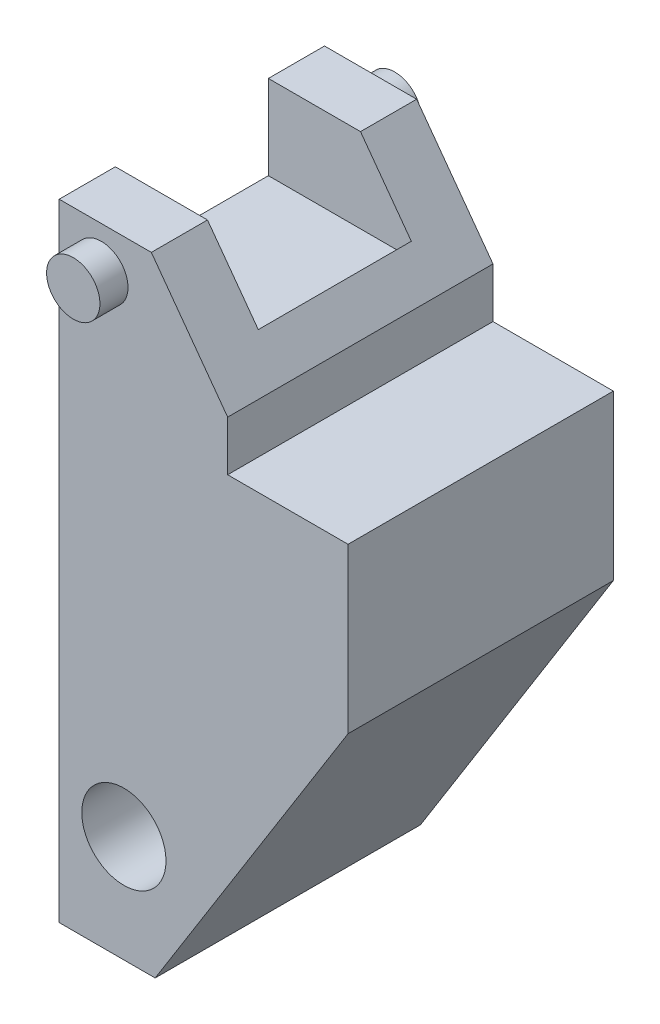
SolidWorks part; units mm, degrees
ref_plane "Front Plane" through (0, 0, 0) normal (0, 0, 1) x (1, 0, 0)
ref_plane "Top Plane" through (0, 0, 0) normal (0, 1, 0) x (1, 0, 0)
ref_plane "Right Plane" through (0, 0, 0) normal (1, 0, 0) x (0, 0, -1)
sketch "Sketch1" plane through (0, 0, 0) normal (0, 0, 1) x (1, 0, 0)
  line L1 (-1.2284, 16.3534) -> (19.3477, 16.3534)
  line L2 (-1.2284, 16.3534) -> (-1.2284, -17.2747)
  line L3 (-1.2284, -17.2747) -> (19.3477, -17.2747)
  line L4 (19.3477, 16.3534) -> (19.3477, -17.2747)
  circle A0 centre (8.5253, 7.418) radius 5.1
  circle A1 centre (3.3782, -9.6738) radius 1.6
  dimension "D1" = 17.85
  dimension "D2" = 10.2
  dimension "D3" = 3.2
extrude "Boss-Extrude1" add sketch "Sketch1" along normal blind 18.9
sketch "Sketch3" plane through (0, 16.3534, 0) normal (0, 1, 0) x (1, 0, 0)
  line L0 (19.3477, -18.9) -> (-1.2284, -18.9) construction
  line L1 (-1.2284, 0) -> (10.7716, 0)
  line L2 (-1.2284, 0) -> (-1.2284, -18.9)
  line L3 (-1.2284, -18.9) -> (10.7716, -18.9)
  line L4 (10.7716, 0) -> (10.7716, -18.9)
  dimension "D1" = 12
extrude "Boss-Extrude3" add sketch "Sketch3" along normal blind 11
sketch "Sketch4" plane through (0, 0, 18.9) normal (0, 0, 1) x (1, 0, 0)
  line L0 (-1.2284, 27.3534) -> (10.7716, 27.3534) construction
  line L1 (-1.2284, 27.3534) -> (-1.2284, -17.2747) construction
  circle A0 centre (1.7716, 24.3534) radius 1.9
  dimension "D1" = 3.8
  dimension "D2" = 3
  dimension "D3" = 3
extrude "Boss-Extrude6" add sketch "Sketch4" along normal blind 2
sketch "Sketch5" plane through (0, 0, 0) normal (0, 0, -1) x (-1, 0, 0)
  line L0 (1.2284, 27.3534) -> (1.2284, -17.2747) construction
  line L1 (-10.7716, 27.3534) -> (1.2284, 27.3534) construction
  circle A0 centre (-1.7716, 24.3534) radius 1.9
  dimension "D1" = 3.8
  dimension "D2" = 3
  dimension "D3" = 3
extrude "Boss-Extrude7" add sketch "Sketch5" along normal blind 2
sketch "Sketch6" plane through (0, 0, 18.9) normal (0, 0, 1) x (1, 0, 0)
  line L0 (5.6068, -17.2747) -> (19.3477, 4.6661)
  line L1 (-1.2284, -17.2747) -> (19.3477, -17.2747) construction
  line L2 (19.3477, -17.2747) -> (19.3477, 16.3534) construction
  line L3 (19.3477, 4.6661) -> (19.3477, -17.2747)
  line L4 (19.3477, -17.2747) -> (5.6068, -17.2747)
extrude "Cut-Extrude1" cut sketch "Sketch6" against normal through all
sketch "Sketch7" plane through (0, 0, 18.9) normal (0, 0, 1) x (1, 0, 0)
  line L0 (5.3343, 27.3534) -> (10.7716, 19.9086)
  line L1 (-1.2284, 27.3534) -> (10.7716, 27.3534) construction
  line L2 (10.7716, 27.3534) -> (10.7716, 16.3534) construction
  line L3 (10.7716, 19.9086) -> (10.7716, 27.3534)
  line L4 (10.7716, 27.3534) -> (5.3343, 27.3534)
extrude "Cut-Extrude2" cut sketch "Sketch7" against normal through all
sketch "Sketch8" plane through (0, 27.3534, 0) normal (0, 1, 0) x (1, 0, 0)
  line L0 (-1.2284, 0) -> (-1.2284, -18.9) construction
  line L1 (-1.2284, -14.9) -> (8.9531, -14.9)
  line L2 (-1.2284, -14.9) -> (-1.2284, -4)
  line L3 (-1.2284, -4) -> (8.9531, -4)
  line L4 (8.9531, -14.9) -> (8.9531, -4)
  line L5 (5.3343, 0) -> (-1.2284, 0) construction
  line L6 (-1.2284, -18.9) -> (5.3343, -18.9) construction
  dimension "D1" = 4
  dimension "D2" = 4
extrude "Cut-Extrude3" cut sketch "Sketch8" against normal blind 6
sketch "Sketch9" plane through (0, 0, 18.9) normal (0, 0, 1) x (1, 0, 0)
  circle A0 centre (8.5253, 7.418) radius 6.1444
extrude "Boss-Extrude8" add sketch "Sketch9" against normal blind 10
sketch "Sketch10" plane through (0, 0, 18.9) normal (0, 0, 1) x (1, 0, 0)
  circle A0 centre (3.3782, -9.6738) radius 3
  dimension "D1" = 6
extrude "Cut-Extrude4" cut sketch "Sketch10" against normal blind 6
